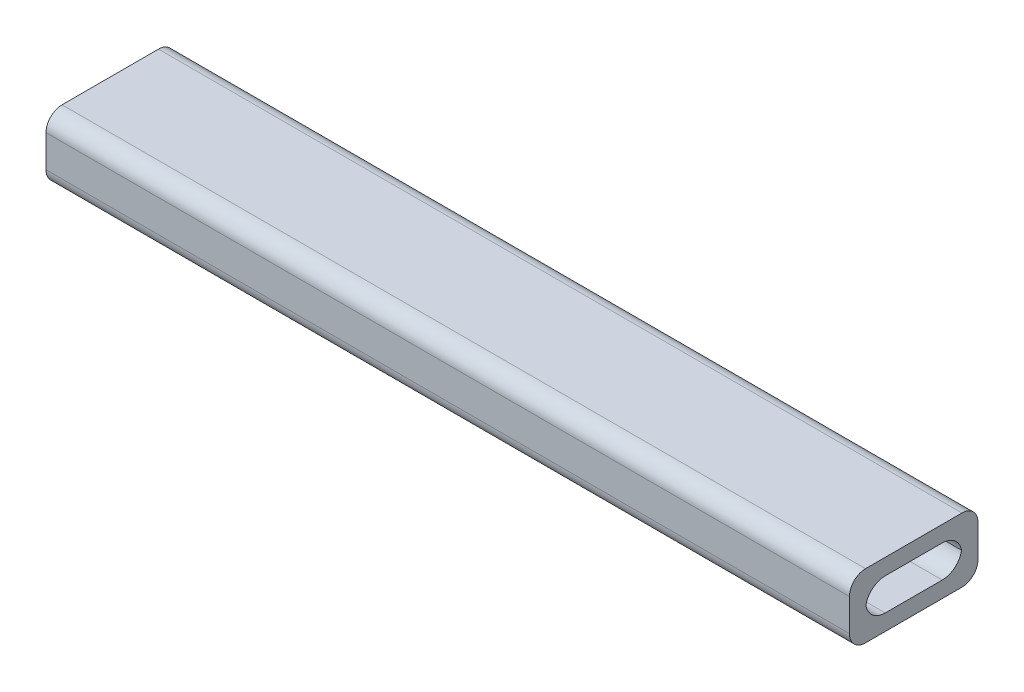
SolidWorks part; units mm, degrees
ref_plane "Front Plane" through (0, 0, 0) normal (0, 0, 1) x (1, 0, 0)
ref_plane "Top Plane" through (0, 0, 0) normal (0, 1, 0) x (1, 0, 0)
ref_plane "Right Plane" through (0, 0, 0) normal (1, 0, 0) x (0, 0, -1)
sketch "Sketch1" plane through (0, 0, 0) normal (1, 0, 0) x (0, 0, -1)
  line L0 (0, 29.6522) -> (0, -37.3043) construction
  line L2 (-8.8703, 5) -> (8.8703, 5)
  line L4 (-8.8703, -5) -> (8.8703, -5)
  line L6 (-15, 5) -> (15, -5) construction
  line L7 (-15, -5) -> (15, 5) construction
  line L8 (-15, 10) -> (15, 10)
  line L9 (-20, 5) -> (-20, -5)
  line L10 (-15, -10) -> (15, -10)
  line L11 (20, 5) -> (20, -5)
  line L12 (-20, 10) -> (20, -10) construction
  line L13 (-20, -10) -> (20, 10) construction
  arc A0 (-20, 5) -> (-15, 10) centre (-15, 5) cw
  arc A1 (20, 5) -> (15, 10) centre (15, 5) ccw
  arc A2 (15, -10) -> (20, -5) centre (15, -5) ccw
  arc A3 (-20, -5) -> (-15, -10) centre (-15, -5) ccw
  arc A4 (14.895, 0) -> (8.8703, -5) centre (8.8703, 1.1297) cw
  arc A5 (14.895, 0) -> (8.8703, 5) centre (8.8703, -1.1297) ccw
  arc A6 (-14.895, 0) -> (-8.8703, 5) centre (-8.8703, -1.1297) cw
  arc A7 (-14.895, 0) -> (-8.8703, -5) centre (-8.8703, 1.1297) ccw
  point P3 (0, 0)
  point P8 (0, 0)
  dimension "D5" = 5
  dimension "D6" = 5
  dimension "D7" = 6.1297
  dimension "D1" = 40
  dimension "D2" = 20
  dimension "D3" = 10
  dimension "D4" = 30
extrude "Boss-Extrude1" add sketch "Sketch1" along normal mid plane 250
